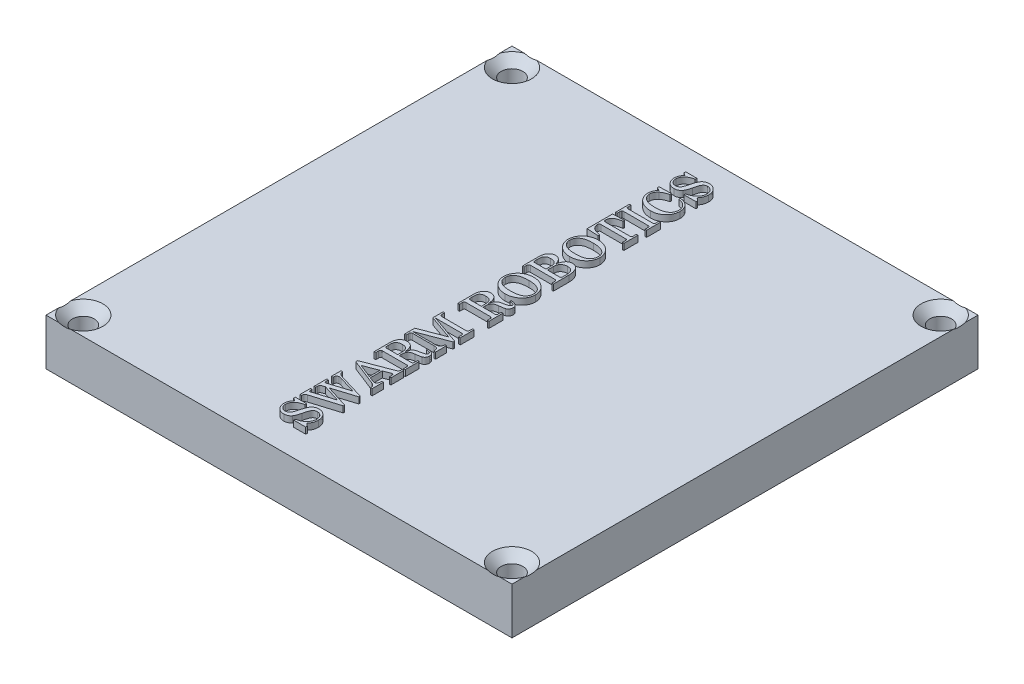
SolidWorks part; units mm, degrees
ref_plane "Front Plane" through (0, 0, 0) normal (0, 0, 1) x (1, 0, 0)
ref_plane "Top Plane" through (0, 0, 0) normal (0, 1, 0) x (1, 0, 0)
ref_plane "Right Plane" through (0, 0, 0) normal (1, 0, 0) x (0, 0, -1)
sketch "Sketch1" plane through (0, 0, 0) normal (0, 1, 0) x (1, 0, 0)
  line L1 (-75, 75) -> (75, 75)
  line L2 (-75, 75) -> (-75, -75)
  line L3 (-75, -75) -> (75, -75)
  line L4 (75, 75) -> (75, -75)
  line L5 (-75, 75) -> (75, -75) construction
  line L6 (-75, -75) -> (75, 75) construction
  point P0 (0, 0)
  dimension "D1" = 150
  dimension "D2" = 150
extrude "Boss-Extrude1" add sketch "Sketch1" along normal blind 15
sketch "Sketch3" plane through (0, 15, 0) normal (0, 1, 0) x (1, 0, 0)
  line L0 (75, 75) -> (-75, 75) construction
  line L3 (75, -75) -> (75, 75) construction
  circle A0 centre (69, 69) radius 3
  dimension "D1" = 6
  dimension "D2" = 6
  dimension "D3" = 6
hole_wizard "CSK for M6 Oval Head Machine Screw2" positions "3DSketch1" profile "Sketch8" countersink size "M6" standard "ANSI Metric" end condition through all
sketch3d "3DSketch1"
  point P0 (69, 15, -69)
sketch "Sketch8" plane through (69, 15, -69) normal (1, 0, 0) x (0, 0, 1)
  line L0 (0, 0) -> (0, 15)
  line L1 (0, 15) -> (3.5, 15)
  line L2 (3.5, 15) -> (3.5, 2.8)
  line L3 (3.5, 2.8) -> (6.3, 0)
  line L5 (6.3, 0) -> (0, 0)
  line L6 (-3.5, 2.8) -> (-6.3, 0) construction
  line L11 (0, -6.35) -> (0, 107.95) construction
  dimension "Thru Hole Dia." = 7
  dimension "Thru Hole Depth" = 15
  dimension "Near C'Sink Dia." = 12.6
  dimension "Near C'Sink Angle" = 90
mirror "Mirror1" about plane through (0, 0, 0) normal (1, 0, 0) of "CSK for M6 Oval Head Machine Screw2"
mirror "Mirror2" about plane through (0, 0, 0) normal (0, 0, 1) of "Mirror1", "CSK for M6 Oval Head Machine Screw2"
sketch "Sketch9" plane through (0, 15, 0) normal (0, 1, 0) x (1, 0, 0)
  line L0 (0, -75) -> (0, 75) construction
  line L1 (-67.0791, -75) -> (67.0791, -75) construction
  line L2 (67.0791, 75) -> (-67.0791, 75) construction
  text T0 "SWARM ROBOTICS" font "Century Schoolbook" height 10
extrude "Boss-Extrude2" add sketch "Sketch9" along normal blind 2
